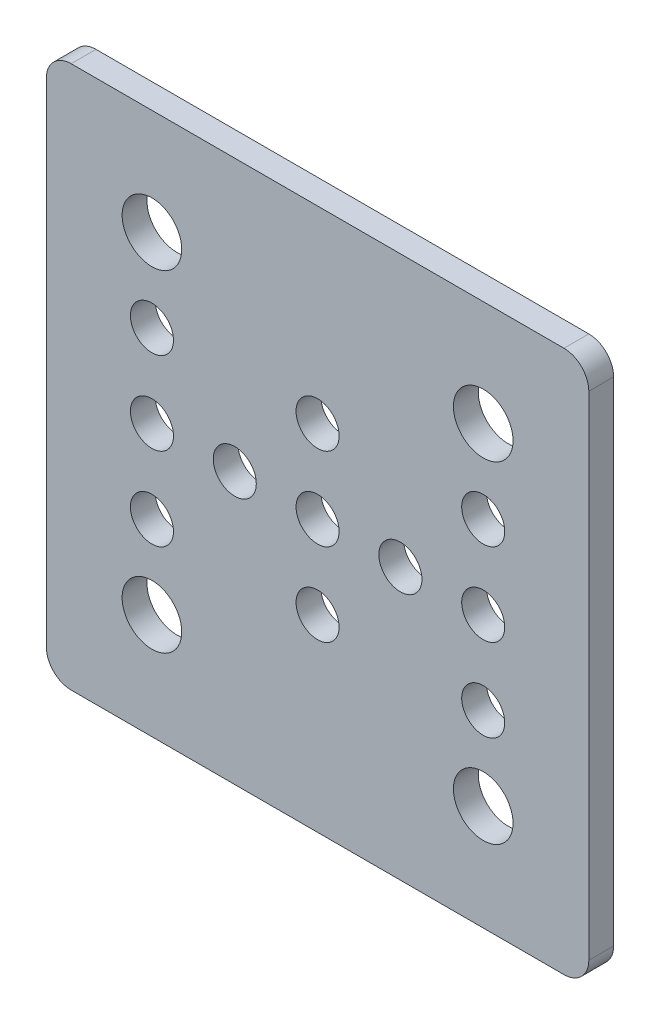
SolidWorks part; units mm, degrees
ref_plane "Front Plane" through (0, 0, 0) normal (0, 0, 1) x (1, 0, 0)
ref_plane "Top Plane" through (0, 0, 0) normal (0, 1, 0) x (1, 0, 0)
ref_plane "Right Plane" through (0, 0, 0) normal (1, 0, 0) x (0, 0, -1)
sketch "Sketch1" plane through (0, 0, 0) normal (0, 0, 1) x (1, 0, 0)
  line L1 (-32.75, 32.75) -> (32.75, 32.75)
  line L2 (-32.75, 32.75) -> (-32.75, -32.75)
  line L3 (-32.75, -32.75) -> (32.75, -32.75)
  line L4 (32.75, 32.75) -> (32.75, -32.75)
  line L5 (-32.75, 32.75) -> (32.75, -32.75) construction
  line L6 (-32.75, -32.75) -> (32.75, 32.75) construction
  point P0 (0, 0)
  dimension "D1" = 65.5
  dimension "D2" = 65.5
extrude "Boss-Extrude1" add sketch "Sketch1" along normal blind 3 contours L2 L3 L4 L1
sketch "Sketch2" plane through (0, 0, 3) normal (0, 0, 1) x (1, 0, 0)
  line L0 (0, 0) -> (10, 0) construction
  line L1 (0, 0) -> (0, -10) construction
  line L2 (0, 0) -> (32.75, 0) construction
  line L3 (32.75, 32.75) -> (32.75, -32.75) construction
  line L4 (0, 0) -> (0, -32.75) construction
  line L5 (-32.75, -32.75) -> (32.75, -32.75) construction
  line L6 (-20, 20) -> (20, 20) construction
  line L7 (-20, 20) -> (-20, -20) construction
  circle A0 centre (0, 0) radius 2.6
  circle A1 centre (10, 0) radius 2.6
  circle A2 centre (20, 0) radius 2.6
  circle A3 centre (0, -10) radius 2.6
  circle A4 centre (20, -10) radius 2.6
  circle A5 centre (20, 10) radius 2.6
  circle A6 centre (0, 10) radius 2.6
  circle A7 centre (-20, -10) radius 2.6
  circle A8 centre (-20, 10) radius 2.6
  circle A9 centre (-20, 0) radius 2.6
  circle A10 centre (-10, 0) radius 2.6
  circle A11 centre (-20, 20) radius 3.6
  circle A12 centre (20, 20) radius 3.6
  circle A13 centre (20, -20) radius 3.6
  circle A14 centre (-20, -20) radius 3.6
  dimension "D1" = 5.2
  dimension "D7" = 7.2
  dimension "D3" = 10
  dimension "D5" = 10
  dimension "D6" = 10
  dimension "D10" = 90
  dimension "D11" = 40
  dimension "D12" = 40
  dimension "D2" = 3
  dimension "D4" = 2
  dimension "D8" = 2
  dimension "D9" = 2
extrude "Cut-Extrude1" cut sketch "Sketch2" against normal up to next
fillet "Fillet1" radius 3 4 edges at (32.75, 32.75, 1.5) (32.75, -32.75, 1.5) (-32.75, -32.75, 1.5) (-32.75, 32.75, 1.5)
